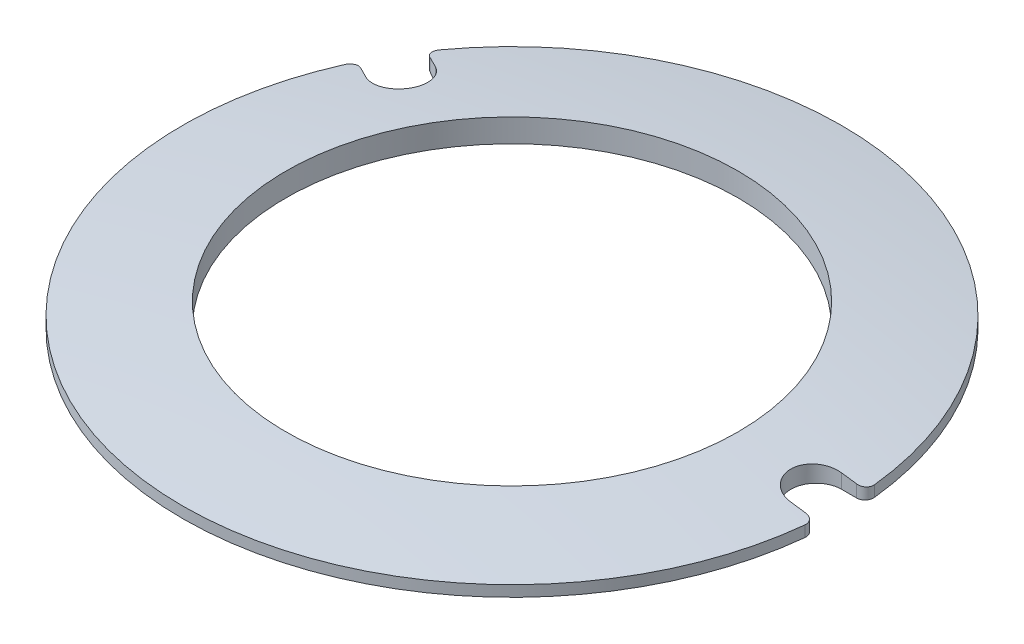
SolidWorks part; units mm, degrees
ref_plane "Front" through (0, 0, 0) normal (0, 0, 1) x (1, 0, 0)
ref_plane "Top" through (0, 0, 0) normal (0, 1, 0) x (1, 0, 0)
ref_plane "Right" through (0, 0, 0) normal (1, 0, 0) x (0, 0, -1)
sketch "Sketch1" plane through (0, 0, 0) normal (0, 0, 1) x (1, 0, 0)
  line L0 (0, 0) -> (0, 278.75) construction
  line L1 (39, 0) -> (39, 278.75) construction
  line L2 (39, 274.7083) -> (26.75, 274.7083)
  line L3 (0, 274.7083) -> (0, 278.75) construction
  line L4 (39, 276.0083) -> (39, 274.7083)
  line L5 (26.75, 277.4635) -> (26.75, 274.7083)
  line L7 (26.75, 274.7083) -> (0, 274.7083) construction
  arc A0 (39, 276.0083) -> (26.75, 277.4635) centre (0, 0) ccw
  arc A1 (26.75, 277.4635) -> (0, 278.75) centre (0, 0) ccw construction
  dimension "D3" = 1.3
  dimension "D1" = 278.75
  dimension "D4" = 26.75
  dimension "D2" = 39
revolve "Revolve1" add sketch "Sketch1" angle 360 about L0
sketch "Sketch2" plane through (0, 0, 0) normal (0, 1, 0) x (1, 0, 0)
  line L0 (36, 0) -> (46, 0) construction
  line L1 (36, 3) -> (46, 3)
  line L2 (36, -3) -> (46, -3)
  line L3 (-31.1769, 18) -> (-39.8372, 23) construction
  line L4 (-32.6769, 15.4019) -> (-41.3372, 20.4019)
  line L5 (-29.6769, 20.5981) -> (-38.3372, 25.5981)
  line L6 (0, 0) -> (36, 0) construction
  line L7 (0, 0) -> (-31.1769, 18) construction
  arc A2 (36, 3) -> (36, -3) centre (36, 0) ccw
  arc A3 (46, -3) -> (46, 3) centre (46, 0) ccw
  arc A4 (-32.6769, 15.4019) -> (-29.6769, 20.5981) centre (-31.1769, 18) ccw
  arc A5 (-38.3372, 25.5981) -> (-41.3372, 20.4019) centre (-39.8372, 23) ccw
  point P2 (41, 0)
  point P13 (-35.507, 20.5)
  dimension "D1" = 6
  dimension "D3" = 150
  dimension "D4" = 36
  dimension "D2" = 10
extrude "Cut-Extrude2" cut sketch "Sketch2" along normal through all
fillet "Fillet1" radius 1 4 edges at (-35.1749, 275.3583, -16.8441) (-32.1749, 275.3583, -22.0403) (38.8844, 275.3583, 3) (38.8844, 275.3583, -3)
